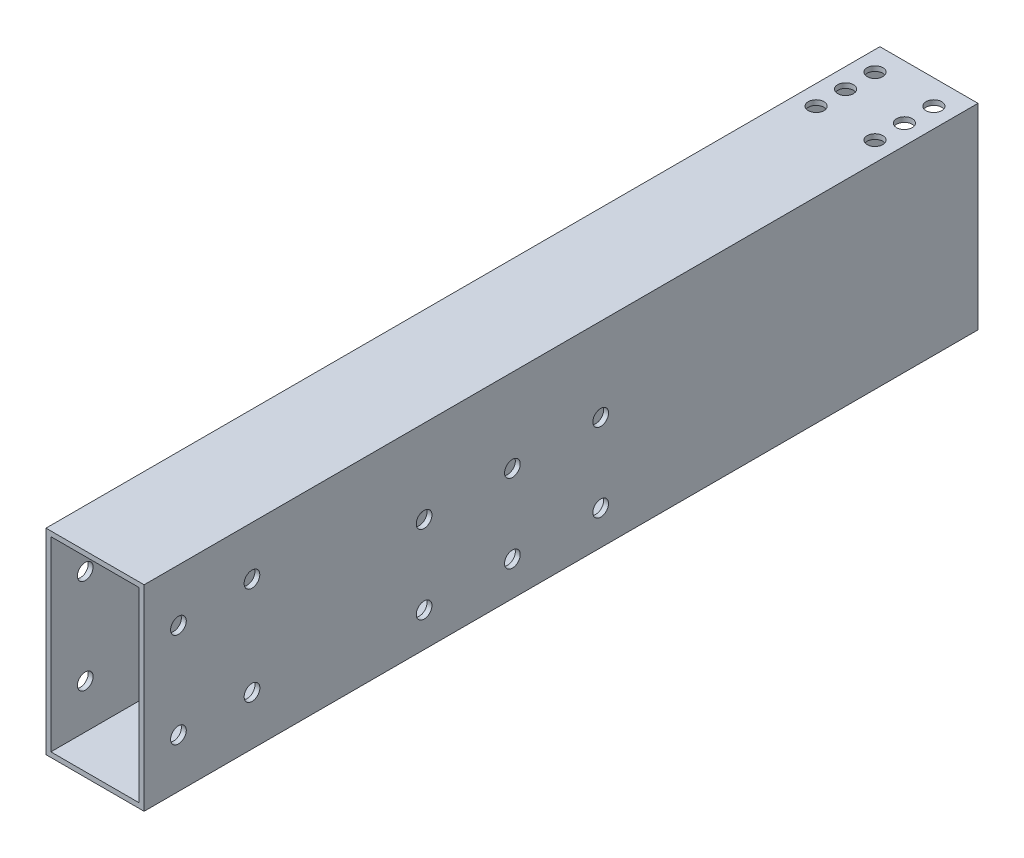
SolidWorks part; units mm, degrees
material "1060-H18 棒材(SS)"
ref_plane "前视基准面" through (0, 0, 0) normal (0, 0, 1) x (1, 0, 0)
ref_plane "上视基准面" through (0, 0, 0) normal (0, 1, 0) x (1, 0, 0)
ref_plane "右视基准面" through (0, 0, 0) normal (1, 0, 0) x (0, 0, -1)
other "Configuration Table"
sketch "草图1" plane through (0, 0, 0) normal (0, 0, 1) x (1, 0, 0)
  line L1 (0, 0) -> (20, 0)
  line L2 (0, 0) -> (0, 40)
  line L3 (0, 40) -> (20, 40)
  line L4 (20, 0) -> (20, 40)
  line L5 (1, 1) -> (19, 1)
  line L6 (1, 1) -> (1, 39)
  line L7 (1, 39) -> (19, 39)
  line L8 (19, 1) -> (19, 39)
  dimension "D1" = 20
  dimension "D2" = 40
  dimension "D3" = 1
  dimension "D4" = 1
  dimension "D5" = 1
  dimension "D6" = 1
extrude "凸台-拉伸1" add sketch "草图1" along normal blind 170
sketch "草图12" plane through (0, 0, 0) normal (-1, 0, 0) x (0, 0, 1)
  line L0 (170, 40) -> (170, 0) construction
  line L1 (170, 0) -> (0, 0) construction
  line L2 (112.92, 23) -> (112.92, 7) construction
  line L3 (112.92, 7) -> (94.92, 7) construction
  circle A0 centre (112.92, 7) radius 1.6
  circle A1 centre (94.92, 7) radius 1.6
  circle A2 centre (76.92, 7) radius 1.6
  circle A3 centre (94.92, 23) radius 1.6
  circle A4 centre (76.92, 23) radius 1.6
  circle A5 centre (112.92, 23) radius 1.6
  dimension "D3" = 3.2
  dimension "D4" = 3
  dimension "D1" = 57.08
  dimension "D2" = 7
  dimension "D6" = 16
  dimension "D7" = 18
  dimension "D8" = 90
  dimension "D5" = 2
extrude "切除-拉伸2" cut sketch "草图12" against normal through all
sketch "草图13" plane through (0, 0, 0) normal (-1, 0, 0) x (0, 0, 1)
  line L0 (170, 40) -> (170, 0) construction
  line L1 (170, 0) -> (0, 0) construction
  circle A0 centre (163, 29.3431) radius 1.6
  circle A1 centre (163, 10) radius 1.6
  circle A2 centre (148.0144, 30) radius 1.6
  circle A3 centre (148, 10) radius 1.6
  dimension "D5" = 3.2
  dimension "D1" = 7
  dimension "D2" = 7
  dimension "D3" = 29.3431
  dimension "D4" = 10
  dimension "D6" = 15
  dimension "D7" = 15
  dimension "D8" = 30
  dimension "D9" = 10
extrude "切除-拉伸3" cut sketch "草图13" against normal through all
sketch "草图14" plane through (0, 40, 0) normal (0, 1, 0) x (1, 0, 0)
  line L0 (0, -170) -> (0, 0) construction
  line L1 (20, -170) -> (20, 0) construction
  line L2 (20, 0) -> (0, 0) construction
  circle A0 centre (16, -11) radius 1.6
  circle A1 centre (4, -11) radius 1.6
  circle A2 centre (16, -5) radius 1.6
  circle A3 centre (4, -5) radius 1.6
  circle A4 centre (16, -17) radius 1.6
  circle A5 centre (4, -17) radius 1.6
  point P18 (16, -17)
  point P19 (4, -17)
  point P20 (16, -17)
  dimension "D1" = 3.2
  dimension "D2" = 12
  dimension "D3" = 4
  dimension "D4" = 4
  dimension "D5" = 4
  dimension "D6" = 12
  dimension "D7" = 6
  dimension "D8" = 5
  dimension "D9" = 5
  dimension "D10" = 6
  dimension "D11" = 6
  dimension "D12" = 4
  dimension "D13" = 4
extrude "切除-拉伸4" cut sketch "草图14" against normal through all
